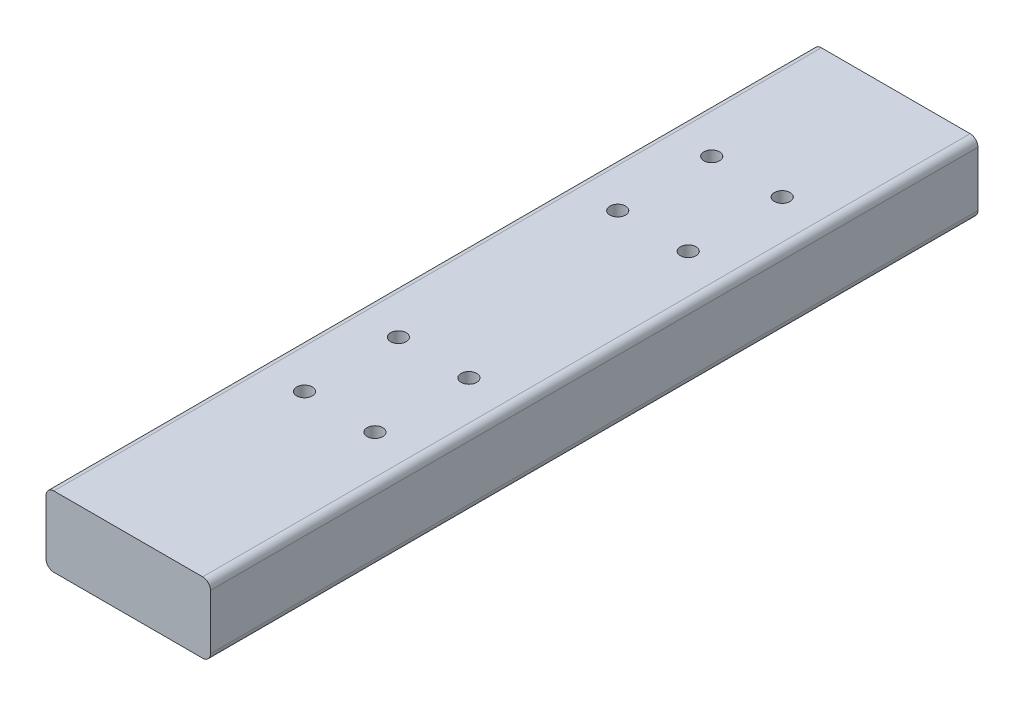
SolidWorks part; units mm, degrees
ref_plane "Front Plane" through (0, 0, 0) normal (0, 0, 1) x (1, 0, 0)
ref_plane "Top Plane" through (0, 0, 0) normal (0, 1, 0) x (1, 0, 0)
ref_plane "Right Plane" through (0, 0, 0) normal (1, 0, 0) x (0, 0, -1)
sketch "Sketch1" plane through (0, 0, 0) normal (0, 0, 1) x (1, 0, 0)
  line L1 (0, 0) -> (42, 0)
  line L2 (0, 0) -> (0, 18)
  line L3 (0, 18) -> (42, 18)
  line L4 (42, 0) -> (42, 18)
  dimension "D1" = 42
  dimension "D2" = 18
extrude "Boss-Extrude1" add sketch "Sketch1" along normal blind 196
fillet "Fillet1" radius 2 4 edges at (0, 0, 98) (42, 0, 98) (42, 18, 98) (0, 18, 98)
sketch "Sketch2" plane through (0, 0, 0) normal (0, -1, 0) x (1, 0, 0)
  line L0 (21, 196) -> (21, 0) construction
  line L1 (2, 196) -> (40, 196) construction
  line L2 (2, 0) -> (40, 0) construction
  line L4 (12, 118) -> (30, 118) construction
  line L5 (12, 118) -> (12, 142) construction
  line L6 (12, 142) -> (30, 142) construction
  line L7 (30, 118) -> (30, 142) construction
  line L8 (12, 118) -> (30, 142) construction
  line L9 (12, 142) -> (30, 118) construction
  line L10 (12, 38) -> (30, 38) construction
  line L11 (12, 38) -> (12, 62) construction
  line L12 (12, 62) -> (30, 62) construction
  line L13 (30, 38) -> (30, 62) construction
  line L14 (12, 38) -> (30, 62) construction
  line L15 (12, 62) -> (30, 38) construction
  circle A0 centre (12, 142) radius 2
  circle A1 centre (30, 142) radius 2
  circle A2 centre (12, 118) radius 2
  circle A3 centre (30, 118) radius 2
  circle A4 centre (12, 62) radius 2
  circle A5 centre (30, 62) radius 2
  circle A6 centre (30, 38) radius 2
  circle A7 centre (12, 38) radius 2
  point P6 (21, 130)
  point P11 (21, 50)
  dimension "D1" = 4
  dimension "D2" = 18
  dimension "D3" = 24
  dimension "D4" = 80
  dimension "D5" = 50
extrude "Cut-Extrude1" cut sketch "Sketch2" against normal through all
